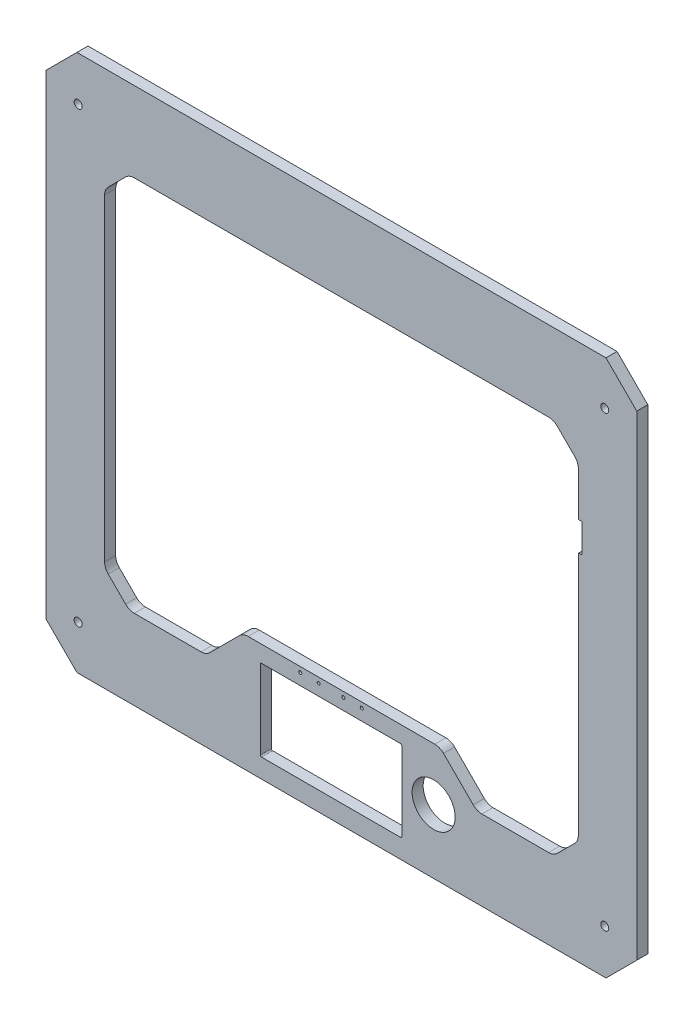
SolidWorks part; units mm, degrees
ref_plane "Front" through (0, 0, 0) normal (0, 0, 1) x (1, 0, 0)
ref_plane "Top" through (0, 0, 0) normal (0, 1, 0) x (1, 0, 0)
ref_plane "Right" through (0, 0, 0) normal (1, 0, 0) x (0, 0, -1)
sketch "Sketch1" plane through (0, 0, 0) normal (0, 0, 1) x (1, 0, 0)
  line L0 (-240, -193.25) -> (-215, -218.25)
  line L1 (-215, -218.25) -> (215, -218.25)
  line L2 (215, -218.25) -> (240, -193.25)
  line L3 (240, -193.25) -> (240, 193.25)
  line L4 (240, 193.25) -> (215, 218.25)
  line L5 (215, 218.25) -> (-215, 218.25)
  line L6 (-215, 218.25) -> (-240, 193.25)
  line L7 (-240, 193.25) -> (-240, -193.25)
  line L8 (-240, 0) -> (240, 0) construction
  line L9 (0, 218.25) -> (0, -218.25) construction
  dimension "D1" = 436.5
  dimension "D2" = 480
  dimension "D3" = 25
  dimension "D4" = 45
extrude "Boss-Extrude1" add sketch "Sketch1" against normal blind 9
sketch "Sketch2" plane through (0, 0, -9) normal (0, 0, -1) x (-1, 0, 0)
  line L0 (114.1421, -153.25) -> (168.3579, -153.25)
  line L1 (175.4289, -150.3211) -> (189.5711, -136.1789)
  line L2 (192.5, -129.1079) -> (192.5, 129.1079)
  line L3 (189.5711, 136.1789) -> (175.4289, 150.3211)
  line L4 (168.3579, 153.25) -> (-168.3579, 153.25)
  line L5 (-175.4289, 150.3211) -> (-189.5711, 136.1789)
  line L6 (-192.5, 129.1079) -> (-192.5, -129.1079)
  line L7 (-189.5711, -136.1789) -> (-175.4289, -150.3211)
  line L8 (-168.3579, -153.25) -> (-114.1421, -153.25)
  line L9 (-107.0711, -150.3211) -> (-82.9289, -126.1789)
  line L10 (-75.8579, -123.25) -> (75.8579, -123.25)
  line L11 (82.9289, -126.1789) -> (107.0711, -150.3211)
  line L12 (0, -123.25) -> (0, 153.25) construction
  line L13 (192.5, 0) -> (-192.5, 0) construction
  arc A0 (168.3579, -153.25) -> (175.4289, -150.3211) centre (168.3579, -143.25) ccw
  arc A1 (189.5711, -136.1789) -> (192.5, -129.1079) centre (182.5, -129.1079) ccw
  arc A2 (192.5, 129.1079) -> (189.5711, 136.1789) centre (182.5, 129.1079) ccw
  arc A3 (175.4289, 150.3211) -> (168.3579, 153.25) centre (168.3579, 143.25) ccw
  arc A4 (-168.3579, 153.25) -> (-175.4289, 150.3211) centre (-168.3579, 143.25) ccw
  arc A5 (-189.5711, 136.1789) -> (-192.5, 129.1079) centre (-182.5, 129.1079) ccw
  arc A6 (-192.5, -129.1079) -> (-189.5711, -136.1789) centre (-182.5, -129.1079) ccw
  arc A7 (-175.4289, -150.3211) -> (-168.3579, -153.25) centre (-168.3579, -143.25) ccw
  arc A8 (-114.1421, -153.25) -> (-107.0711, -150.3211) centre (-114.1421, -143.25) ccw
  arc A9 (-82.9289, -126.1789) -> (-75.8579, -123.25) centre (-75.8579, -133.25) cw
  arc A10 (75.8579, -123.25) -> (82.9289, -126.1789) centre (75.8579, -133.25) cw
  arc A11 (107.0711, -150.3211) -> (114.1421, -153.25) centre (114.1421, -143.25) ccw
  point P41 (0, -43.25)
  dimension "D5" = 10
  dimension "D1" = 385
  dimension "D2" = 306.5
  dimension "D3" = 30
  dimension "D4" = 45
  dimension "D6" = 20
  dimension "D7" = 43.25
extrude "Cut-Extrude1" cut sketch "Sketch2" against normal through all
sketch "Sketch3" plane through (0, 0, -9) normal (0, 0, -1) x (-1, 0, 0)
  line L0 (48, -149.25) -> (-48, -149.25)
  line L1 (-49, -150.25) -> (-49, -189.25)
  line L2 (-48, -190.25) -> (48, -190.25)
  line L3 (49, -189.25) -> (49, -150.25)
  line L4 (0, 0) -> (0, -219.0392) construction
  line L5 (49, -169.75) -> (-49, -169.75) construction
  line L6 (-75.8579, -123.25) -> (75.8579, -123.25) construction
  arc A0 (-48, -149.25) -> (-49, -150.25) centre (-48, -150.25) ccw
  arc A1 (-49, -189.25) -> (-48, -190.25) centre (-48, -189.25) ccw
  arc A2 (48, -190.25) -> (49, -189.25) centre (48, -189.25) ccw
  arc A3 (49, -150.25) -> (48, -149.25) centre (48, -150.25) ccw
  point P17 (0, -169.75)
  dimension "D3" = 1
  dimension "D1" = 41
  dimension "D2" = 98
  dimension "D4" = 26
extrude "Cut-Extrude2" cut sketch "Sketch3" against normal through all
sketch "Sketch6" plane through (0, 0, -9) normal (0, 0, -1) x (-1, 0, 0)
  line L0 (-75.8579, -123.25) -> (75.8579, -123.25) construction
  line L1 (-240, -193.25) -> (-240, 193.25) construction
  circle A0 centre (-74.9, -166.25) radius 17.5
  dimension "D3" = 35
  dimension "D1" = 43
  dimension "D2" = 165.1
extrude "Cut-Extrude3" cut sketch "Sketch6" against normal through all
hole_wizard "Ø6.5 (6.5) Diameter Hole1" positions "Sketch5" profile "Sketch4" hole size "Ø6.5" standard "ANSI Metric"
sketch "Sketch5" plane through (0, 0, 0) normal (0, 0, 1) x (1, 0, 0)
  line L0 (-214, 182.25) -> (214, -182.25) construction
  line L2 (214, 182.25) -> (-214, -182.25) construction
  point P0 (214, -182.25)
  point P1 (-214, -182.25)
  point P2 (-214, 182.25)
  point P3 (214, 182.25)
  dimension "D1" = 428
  dimension "D2" = 364.5
sketch "Sketch4" plane through (214, -182.25, 0) normal (1, 0, 0) x (0, -1, 0)
  line L0 (0, 0) -> (0, 9)
  line L1 (0, 9) -> (3.25, 9)
  line L2 (3.25, 9) -> (3.25, 0)
  line L5 (3.25, 0) -> (0, 0)
  line L11 (0, -6.35) -> (0, 107.95) construction
  dimension "Thru Hole Dia." = 6.5
  dimension "Thru Hole Depth" = 9
sketch "Sketch7" plane through (0, 0, -9) normal (0, 0, -1) x (-1, 0, 0)
  line L0 (-48, -136.75) -> (65, -136.75)
  line L1 (-48, -202.75) -> (65, -202.75)
  line L2 (66, -201.75) -> (66, -137.75)
  line L4 (-49, -201.75) -> (-49, -137.75)
  line L6 (215, -218.25) -> (-215, -218.25) construction
  line L7 (-75.8579, -123.25) -> (75.8579, -123.25) construction
  line L8 (0, 0) -> (0, -231.9961) construction
  arc A0 (66, -137.75) -> (65, -136.75) centre (65, -137.75) ccw
  arc A1 (65, -202.75) -> (66, -201.75) centre (65, -201.75) ccw
  arc A2 (-48, -202.75) -> (-49, -201.75) centre (-48, -201.75) cw
  arc A3 (-49, -137.75) -> (-48, -136.75) centre (-48, -137.75) cw
  dimension "D5" = 1
  dimension "D1" = 15.5
  dimension "D2" = 13.5
  dimension "D3" = 115
  dimension "D4" = 66
extrude "Cut-Extrude4" cut sketch "Sketch7" against normal up to next
sketch "Sketch8" plane through (0, 0, 0) normal (0, 0, 1) x (1, 0, 0)
  line L0 (-65, -136.75) -> (48, -136.75) construction
  line L1 (-33.5, -127.5419) -> (16.5, -127.5419) construction
  line L2 (75.8579, -123.25) -> (-75.8579, -123.25) construction
  line L3 (-8.5, -127.5419) -> (-8.5, -136.75) construction
  circle A1 centre (-33.5, -127.5419) radius 1.25
  circle A3 centre (-18.5, -127.5419) radius 1.25
  circle A5 centre (1.5, -127.5419) radius 1.25
  circle A7 centre (16.5, -127.5419) radius 1.25
  point P15 (-8.5, -136.75)
  dimension "D4" = 2.5
  dimension "D1" = 4.2919
  dimension "D2" = 50
  dimension "D3" = 15
extrude "Cut-Extrude5" cut sketch "Sketch8" against normal up to next
sketch "Sketch9" plane through (0, 0, 0) normal (0, 0, 1) x (1, 0, 0)
  line L0 (192.5, 129.1079) -> (192.5, -129.1079) construction
  line L1 (192.5, 93.25) -> (195.5, 93.25)
  line L2 (192.5, 93.25) -> (192.5, 69.75)
  line L3 (192.5, 69.75) -> (195.5, 69.75)
  line L4 (195.5, 93.25) -> (195.5, 69.75)
  line L6 (215, 218.25) -> (-215, 218.25) construction
  dimension "D1" = 125
  dimension "D2" = 23.5
  dimension "D3" = 3
extrude "Cut-Extrude6" cut sketch "Sketch9" against normal up to next
fillet "Fillet1" radius 0.5 4 edges at (192.5, 69.75, -4.5) (195.5, 69.75, -4.5) (192.5, 93.25, -4.5) (195.5, 93.25, -4.5)
hole_wizard "M3 Tapped Hole1" positions "Sketch12" profile "Sketch11" tap size "M3" standard "ISO"
sketch "Sketch12" plane through (195.5, 0, 0) normal (-1, 0, 0) x (0, 0, 1)
  line L0 (-9, 81.5) -> (0, 81.5) construction
  line L1 (-9, 92.75) -> (-9, 70.25) construction
  line L2 (0, 70.25) -> (0, 92.75) construction
  point P0 (-4.5, 88.625)
  point P3 (-4.5, 74.375)
  dimension "D1" = 4.5
  dimension "D2" = 14.25
sketch "Sketch11" plane through (195.5, 88.625, -4.5) normal (0, 1, 0) x (0, 0, 1)
  line L0 (0, 0) -> (0, 10.7511)
  line L1 (0, 10.7511) -> (1.25, 10)
  line L2 (1.25, 10) -> (1.25, 0.275)
  line L3 (1.25, 0.275) -> (1.525, 0)
  line L5 (1.525, 0) -> (0, 0)
  line L6 (-1.25, 0.275) -> (-1.525, 0) construction
  line L10 (0, 10.7511) -> (-1.25, 10) construction
  line L11 (0, -6.35) -> (0, 107.95) construction
  dimension "Tap Drill Dia." = 2.5
  dimension "Tap Drill Depth" = 10
  dimension "Near C'Sink Dia." = 3.05
  dimension "Near C'Sink Angle" = 90
  dimension "Drill Angle" = 118
cosmetic thread "Hole Thread1" parameters "D1"=7, "D2"=3
cosmetic thread "Hole Thread2" parameters "D1"=7, "D2"=3
